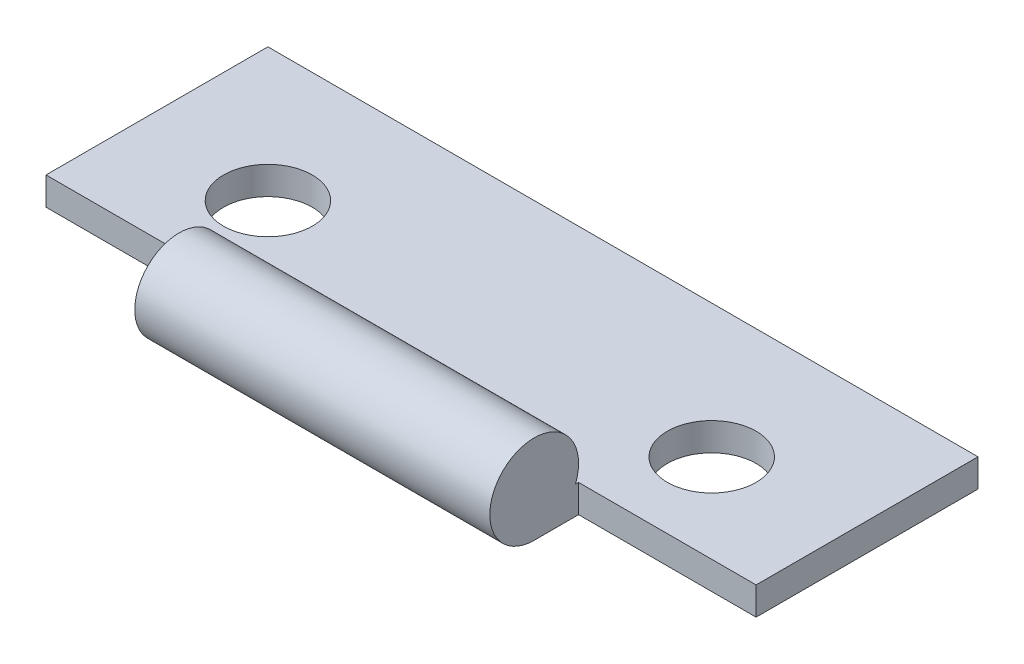
SolidWorks part; units mm, degrees
ref_plane "Front Plane" through (0, 0, 0) normal (0, 0, 1) x (1, 0, 0)
ref_plane "Top Plane" through (0, 0, 0) normal (0, 1, 0) x (1, 0, 0)
ref_plane "Right Plane" through (0, 0, 0) normal (1, 0, 0) x (0, 0, -1)
sketch "Sketch1" plane through (0, 0, 0) normal (0, 1, 0) x (1, 0, 0)
  line L0 (12.7, 9.525) -> (12.7, 0) construction
  line L1 (25.4, 9.525) -> (25.4, 1.5875)
  line L2 (0, 9.525) -> (0, 1.5875)
  line L3 (0, 9.525) -> (25.4, 9.525)
  line L4 (25.4, 1.5875) -> (19.05, 1.5875)
  line L5 (0, 1.5875) -> (6.35, 1.5875)
  line L6 (6.35, 1.5875) -> (6.35, 0)
  line L7 (6.35, 0) -> (19.05, 0)
  line L8 (19.05, 1.5875) -> (19.05, 0)
  circle A0 centre (4.7625, 4.7625) radius 1.5875
  circle A1 centre (20.6375, 4.7625) radius 1.5875
  dimension "D3" = 3.175
  dimension "D1" = 7.9375
  dimension "D2" = 25.4
  dimension "D4" = 6.35
  dimension "D5" = 1.5875
extrude "Boss-Extrude1" add sketch "Sketch1" along normal blind 1
ref_plane "Plane1" through (6.35, 0, 0) normal (-1, 0, 0) x (0, 0, 1)
sketch "Sketch2" plane through (6.35, 0, 0) normal (-1, 0, 0) x (0, 0, 1)
  line L0 (0, 0) -> (0, 1.5875) construction
  line L1 (0, 1) -> (0, 0) construction
  circle A0 centre (0, 1.5875) radius 1.5875
  dimension "D1" = 1.5875
extrude "Boss-Extrude2" add sketch "Sketch2" against normal blind 12.7
